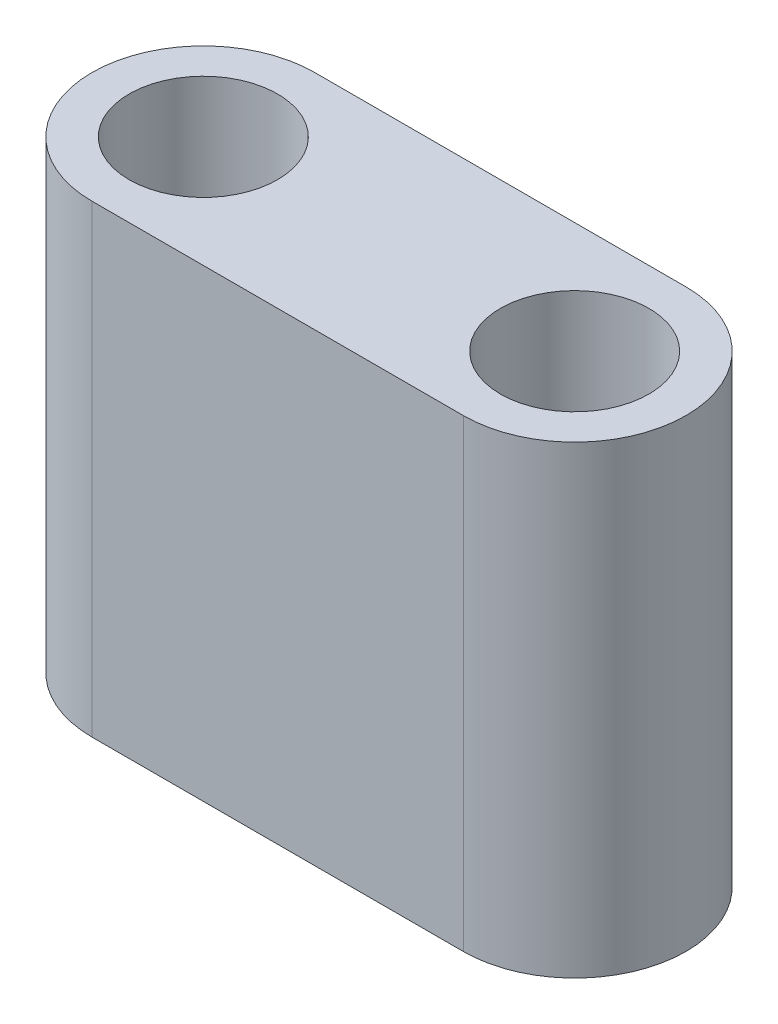
SolidWorks part; units mm, degrees
material "6061 Alloy"
ref_plane "Front Plane" through (0, 0, 0) normal (0, 0, 1) x (1, 0, 0)
ref_plane "Top Plane" through (0, 0, 0) normal (0, 1, 0) x (1, 0, 0)
ref_plane "Right Plane" through (0, 0, 0) normal (1, 0, 0) x (0, 0, -1)
sketch "Sketch1" plane through (0, 0, 0) normal (0, 1, 0) x (1, 0, 0)
  line L0 (-20, 0) -> (20, 0) construction
  line L1 (-20, 12) -> (20, 12)
  line L2 (-20, -12) -> (20, -12)
  circle A0 centre (-20, 0) radius 8
  circle A1 centre (20, 0) radius 8
  arc A2 (-20, 12) -> (-20, -12) centre (-20, 0) ccw
  arc A3 (20, 12) -> (20, -12) centre (20, 0) cw
  point P2 (0, 0)
  dimension "D1" = 40
  dimension "D2" = 16
  dimension "D3" = 12
extrude "Boss-Extrude1" add sketch "Sketch1" against normal blind 50 contours L1 A3 L2 A2
